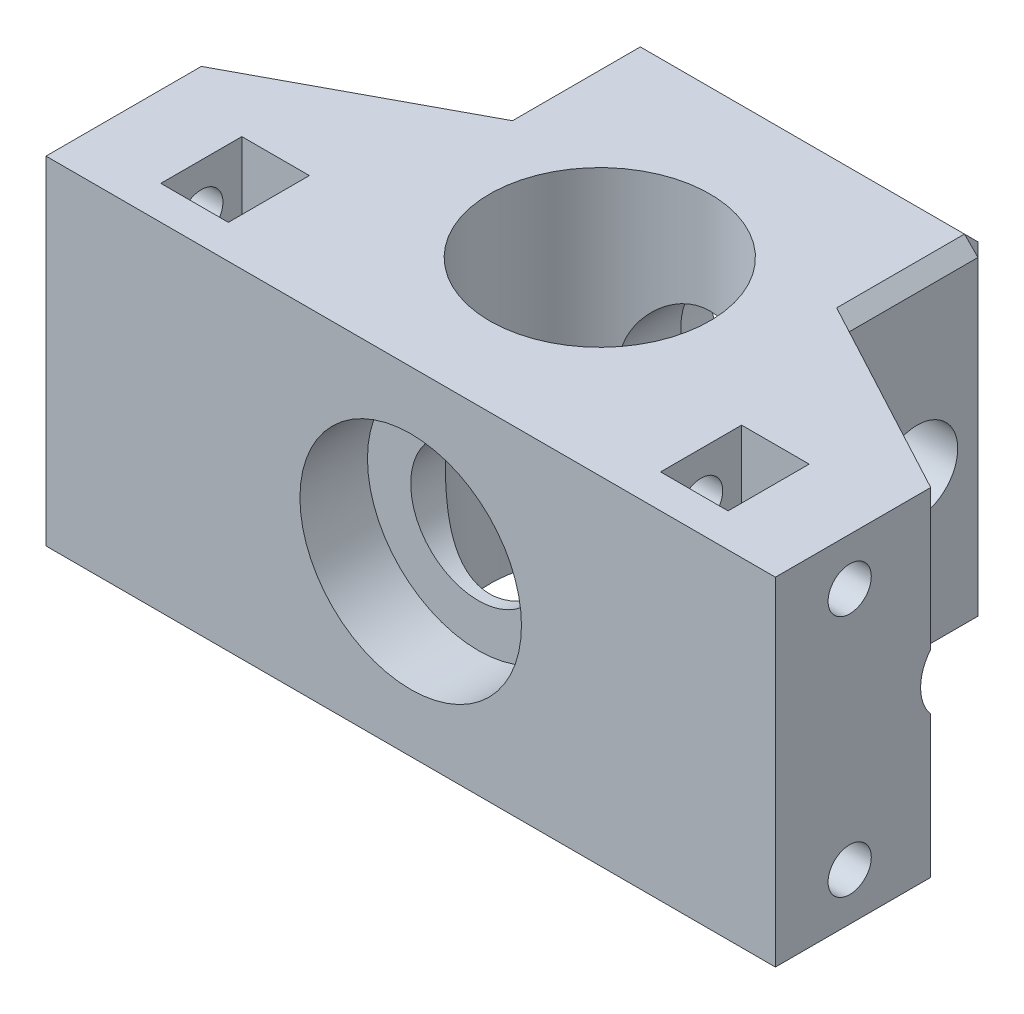
SolidWorks part; units mm, degrees
material "3D printed plastic"
ref_plane "Front Plane" through (0, 0, 0) normal (0, 0, 1) x (1, 0, 0)
ref_plane "Top Plane" through (0, 0, 0) normal (0, 1, 0) x (1, 0, 0)
ref_plane "Right Plane" through (0, 0, 0) normal (1, 0, 0) x (0, 0, -1)
sketch "Sketch1" plane through (0, 0, 0) normal (0, 1, 0) x (1, 0, 0)
  line L0 (0, 14) -> (0, -14) construction
  line L1 (-13, 14) -> (13, 14) construction
  line L2 (-13, 14) -> (-13, 5)
  line L3 (-27, -14) -> (27, -14)
  line L4 (13, 14) -> (13, 5)
  line L5 (13, 5) -> (27, -2.5)
  line L6 (27, -14) -> (27, -2.5)
  line L9 (-13, 5) -> (-27, -2.5)
  line L10 (-27, -14) -> (-27, -2.5)
  line L13 (-13, 14) -> (-13, 16)
  line L14 (-13, 16) -> (13, 16)
  line L15 (13, 16) -> (13, 14)
  circle A0 centre (0, 0) radius 8.15
  dimension "D2" = 16.3
  dimension "D1" = 28
  dimension "D3" = 11.5
  dimension "D4" = 54
  dimension "D5" = 26
  dimension "D8" = 9
  dimension "D9" = 2
extrude "Boss-Extrude1" add sketch "Sketch1" along normal blind 25
sketch "Sketch2" plane through (0, 0, 14) normal (0, 0, 1) x (1, 0, 0)
  line L0 (0, 25) -> (0, 0) construction
  line L1 (-27, 25) -> (27, 25) construction
  circle A0 centre (0, 12.5) radius 5
  dimension "D1" = 10
extrude "Cut-Extrude1" cut sketch "Sketch2" against normal through all
sketch "Sketch3" plane through (0, 0, -16) normal (0, 0, -1) x (-1, 0, 0)
  circle A0 centre (0, 12.5) radius 8.2
  dimension "D1" = 16.4
extrude "Cut-Extrude2" cut sketch "Sketch3" against normal blind 5
sketch "Sketch4" plane through (0, 0, 14) normal (0, 0, 1) x (1, 0, 0)
  circle A0 centre (0, 12.5) radius 8.2
  dimension "D1" = 16.4
extrude "Cut-Extrude3" cut sketch "Sketch4" against normal blind 5
chamfer "Chamfer1" distance 1 angle 45 8 edges at (13, 0, -10.5) (-13, 0, -10.5) (-13, 25, -10.5) (13, 25, -10.5) (-13, 12.5, -16) (0, 0, -16) (13, 12.5, -16) (0, 25, -16)
sketch "Sketch5" plane through (0, 0, 0) normal (1, 0, 0) x (0, 0, -1)
  line L0 (0, 0) -> (0, 12.5461) construction
  line L1 (0, 12.5461) -> (1.5179, 25) construction
  line L2 (-2.5, 25) -> (5.5357, 25) construction
  circle A0 centre (0, 12.5461) radius 1.25
  dimension "D1" = 2.5
extrude "Cut-Extrude4" cut sketch "Sketch5" against normal through all both and the other way through all
sketch "Sketch6" plane through (0, 0, 0) normal (1, 0, 0) x (0, 0, -1)
  circle A0 centre (0, 12.5461) radius 3.25
  dimension "D1" = 6.5
extrude "Cut-Extrude5" cut sketch "Sketch6" against normal through all from offset 13 offset against normal yes
mirror "Mirror1" about plane through (0, 0, 0) normal (1, 0, 0) of "Cut-Extrude5"
sketch "Sketch7" plane through (13, 0, 0) normal (1, 0, 0) x (0, 0, -1)
  line L0 (16, 12.5) -> (10.5, 12.5) construction
  line L1 (16, 24) -> (16, 1) construction
  circle A0 centre (10.5, 12.5) radius 3
  dimension "D1" = 6
  dimension "D2" = 5.5
extrude "Cut-Extrude6" cut sketch "Sketch7" against normal blind 4
sketch "Sketch9" plane through (27, 0, 0) normal (1, 0, 0) x (0, 0, -1)
  line L0 (-8.5, 3.5) -> (-8.5, 21.5) construction
  line L1 (-8.5, 12.5) -> (-14, 12.5) construction
  line L2 (-14, 25) -> (-14, 0) construction
  circle A0 centre (-8.5, 21.5) radius 1.6
  circle A1 centre (-8.5, 3.5) radius 1.6
  dimension "D1" = 3.2
  dimension "D2" = 5.5
  dimension "D3" = 18
extrude "Cut-Extrude7" cut sketch "Sketch9" against normal blind 14
sketch "Sketch10" plane through (27, 0, 0) normal (1, 0, 0) x (0, 0, -1)
  line L0 (-11.5, 19.7679) -> (-11.5, 18.7679)
  line L1 (-8.5, 18.0359) -> (-5.5, 19.7679) construction
  line L2 (-5.5, 19.7679) -> (-5.5, 23.2321)
  line L3 (-5.5, 23.2321) -> (-8.5, 24.9641) construction
  line L4 (-8.5, 24.9641) -> (-11.5, 23.2321) construction
  line L5 (-11.5, 23.2321) -> (-11.5, 19.7679)
  line L6 (-11.5, 19.7679) -> (-8.5, 18.0359) construction
  line L7 (-11.5, 18.7679) -> (-8.5, 17.0359)
  line L8 (-8.5, 17.0359) -> (-5.5, 18.7679)
  line L9 (-5.5, 18.7679) -> (-5.5, 19.7679)
  line L11 (-5.5, 23.2321) -> (-5.5, 25)
  line L12 (-14, 25) -> (-2.5, 25) construction
  line L13 (-5.5, 25) -> (-11.5, 25)
  line L14 (-11.5, 25) -> (-11.5, 23.2321)
  line L15 (-14, 12.5) -> (-10.1547, 12.5) construction
  line L16 (-14, 25) -> (-14, 0) construction
  line L17 (-11.5, 5.2321) -> (-8.5, 6.9641) construction
  line L18 (-8.5, 0.0359) -> (-11.5, 1.7679) construction
  line L19 (-5.5, 1.7679) -> (-8.5, 0.0359) construction
  line L20 (-8.5, 6.9641) -> (-5.5, 5.2321) construction
  line L21 (-11.5, 0) -> (-11.5, 1.7679)
  line L22 (-5.5, 0) -> (-11.5, 0)
  line L23 (-5.5, 1.7679) -> (-5.5, 0)
  line L24 (-5.5, 6.2321) -> (-5.5, 5.2321)
  line L25 (-8.5, 7.9641) -> (-5.5, 6.2321)
  line L26 (-11.5, 6.2321) -> (-8.5, 7.9641)
  line L27 (-11.5, 1.7679) -> (-11.5, 5.2321)
  line L28 (-5.5, 5.2321) -> (-5.5, 1.7679)
  line L29 (-11.5, 5.2321) -> (-11.5, 6.2321)
  circle A0 centre (-8.5, 21.5) radius 3 construction
  circle A1 centre (-8.5, 3.5) radius 3 construction
  dimension "D1" = 6
  dimension "D2" = 1
extrude "Cut-Extrude8" cut sketch "Sketch10" against normal blind 5 from offset 6 offset against normal yes
mirror "Mirror2" about plane through (0, 0, 0) normal (1, 0, 0) of "Cut-Extrude8", "Cut-Extrude7", "Cut-Extrude6"
